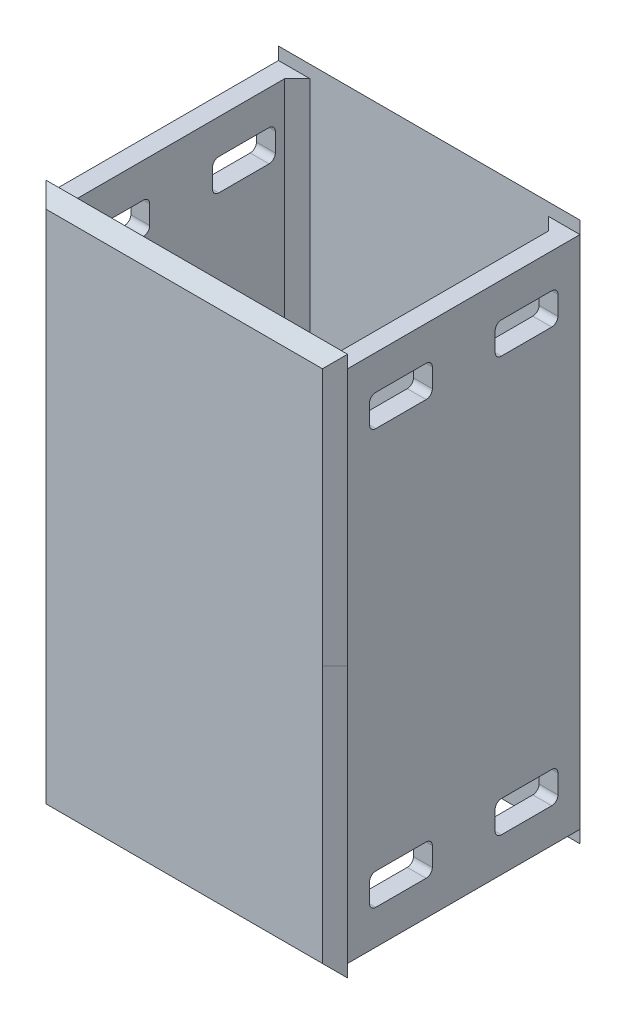
SolidWorks part; units mm, degrees
ref_plane "Front Plane" through (0, 0, 0) normal (0, 0, 1) x (1, 0, 0)
ref_plane "Top Plane" through (0, 0, 0) normal (0, 1, 0) x (1, 0, 0)
ref_plane "Right Plane" through (0, 0, 0) normal (1, 0, 0) x (0, 0, -1)
sketch "Sketch2" plane through (0, 0, 0) normal (0, 1, 0) x (1, 0, 0)
  line L4 (10.5, 9.25) -> (-10.5, 9.25)
  line L5 (-10.5, 9.25) -> (-10.5, -9.25)
  line L6 (-10.5, -9.25) -> (10.5, -9.25)
  line L7 (10.5, -9.25) -> (10.5, 9.25)
  line L8 (-12, -10.25) -> (12, -10.25)
  line L9 (12, -10.25) -> (12, 10.25)
  line L10 (12, 10.25) -> (-12, 10.25)
  line L11 (-12, 10.25) -> (-12, -10.25)
  line L12 (0, 14.2214) -> (0, -14.8607) construction
  line L13 (18.2013, 0) -> (-22.5294, 0) construction
  dimension "D2" = 21
  dimension "D3" = 18.5
  dimension "D1" = 1
  dimension "D4" = 1
  dimension "D5" = 1.5
  dimension "D6" = 1.5
extrude "Boss-Extrude2" add sketch "Sketch2" along normal blind 20.5
sketch "Sketch4" plane through (0, 0, 0) normal (1, 0, 0) x (0, 0, -1)
  line L0 (-10.25, 20.5) -> (-9.25, 21.5)
  line L1 (-9.25, 21.5) -> (-9.25, 20.5)
  line L3 (-9.25, 20.5) -> (-10.25, 20.5)
  line L4 (0, 85.8429) -> (0, -56.1998) construction
  line L5 (10.25, 20.5) -> (9.25, 21.5)
  line L6 (9.25, 20.5) -> (10.25, 20.5)
  line L7 (9.25, 21.5) -> (9.25, 20.5)
  dimension "D1" = 1
extrude "Boss-Extrude5" add sketch "Sketch4" along normal up to surface and the other way up to surface up to face at (12, 10.25, 0) other way up to face at (-12, 10.25, 0)
sketch "Sketch5" plane through (12, 0, 0) normal (1, 0, 0) x (0, 0, -1)
  line L0 (0, 105.7903) -> (0, -108.397) construction
  line L1 (-7, 17.75) -> (-3, 17.75)
  line L2 (-2.5, 17.25) -> (-2.5, 15.75)
  line L3 (-3, 15.25) -> (-7, 15.25)
  line L4 (-7.5, 17.25) -> (-7.5, 15.75)
  line L5 (-9.25, 20.5) -> (9.25, 20.5) construction
  line L6 (7, 17.75) -> (3, 17.75)
  line L7 (7.5, 17.25) -> (7.5, 15.75)
  line L8 (3, 15.25) -> (7, 15.25)
  line L9 (2.5, 17.25) -> (2.5, 15.75)
  arc A0 (-3, 17.75) -> (-2.5, 17.25) centre (-3, 17.25) cw
  arc A1 (-2.5, 15.75) -> (-3, 15.25) centre (-3, 15.75) cw
  arc A2 (-7, 15.25) -> (-7.5, 15.75) centre (-7, 15.75) cw
  arc A3 (-7, 17.75) -> (-7.5, 17.25) centre (-7, 17.25) ccw
  arc A4 (7, 17.75) -> (7.5, 17.25) centre (7, 17.25) cw
  arc A5 (7, 15.25) -> (7.5, 15.75) centre (7, 15.75) ccw
  arc A6 (2.5, 15.75) -> (3, 15.25) centre (3, 15.75) ccw
  arc A7 (3, 17.75) -> (2.5, 17.25) centre (3, 17.25) ccw
  dimension "D5" = 0.5
  dimension "D1" = 5
  dimension "D2" = 2.5
  dimension "D3" = 2.5
  dimension "D4" = 2.75
extrude "Cut-Extrude1" cut sketch "Sketch5" against normal through all
chamfer "Chamfer1" distance 1 angle 45 8 edges at (-12, 10.25, -10.25) (12, 10.25, -10.25) (12, 10.25, 10.25) (-12, 10.25, 10.25) (10.5, 10.25, -9.25) (-10.5, 10.25, -9.25)
mirror "Mirror1" about plane through (0, 0, 0) normal (0, 1, 0) of "Boss-Extrude2", "Boss-Extrude5", "Cut-Extrude1", "Chamfer1"
